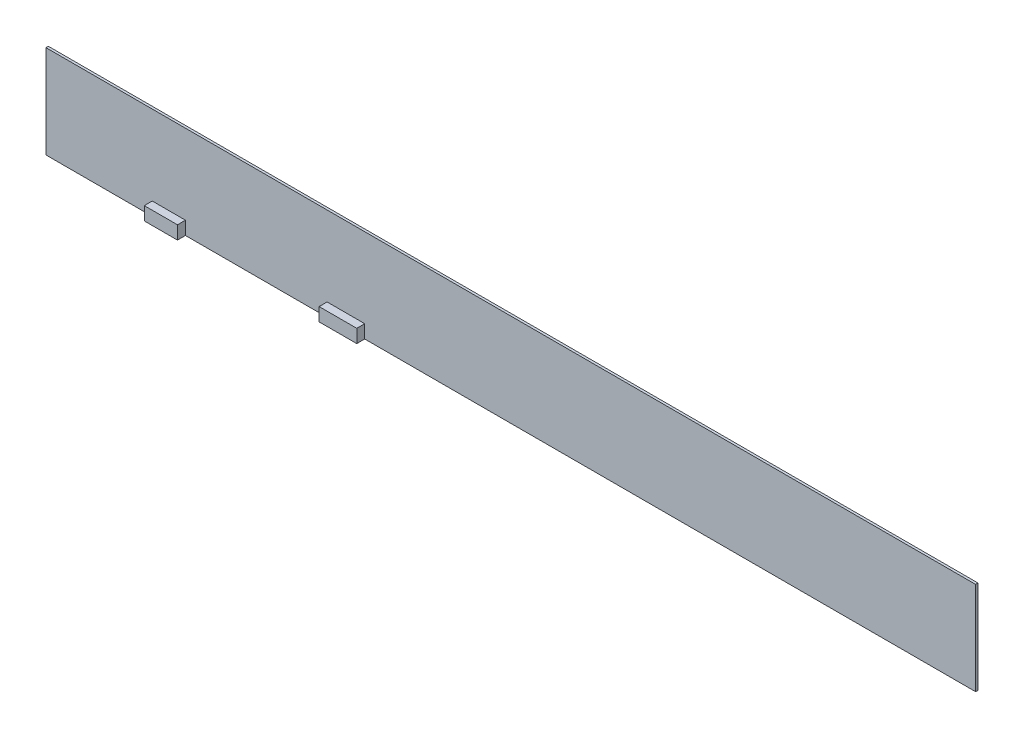
SolidWorks part; units mm, degrees
ref_plane "前视基准面" through (0, 0, 0) normal (0, 0, 1) x (1, 0, 0)
ref_plane "上视基准面" through (0, 0, 0) normal (0, 1, 0) x (1, 0, 0)
ref_plane "右视基准面" through (0, 0, 0) normal (1, 0, 0) x (0, 0, -1)
other "Configuration Table"
sketch "草图1" plane through (0, 0, 0) normal (0, 0, 1) x (1, 0, 0)
  line L1 (0, 0) -> (2100, 0)
  line L2 (0, 0) -> (0, 210)
  line L3 (0, 210) -> (2100, 210)
  line L4 (2100, 0) -> (2100, 210)
  dimension "D1" = 2100
  dimension "D2" = 210
extrude "凸台-拉伸1" add sketch "草图1" along normal blind 5.4
sketch "草图2" plane through (0, 0, 5.4) normal (0, 0, 1) x (1, 0, 0)
  line L0 (0, 0) -> (2100, 0) construction
  line L1 (240, 0) -> (315, 0)
  line L2 (240, 0) -> (240, 30)
  line L3 (240, 30) -> (315, 30)
  line L4 (315, 0) -> (315, 30)
  line L5 (0, 210) -> (0, 0) construction
  line L7 (635, 0) -> (720, 0)
  line L8 (635, 0) -> (635, 30)
  line L9 (635, 30) -> (720, 30)
  line L10 (720, 0) -> (720, 30)
  dimension "D1" = 30
  dimension "D2" = 240
  dimension "D3" = 315
  dimension "D4" = 30
  dimension "D5" = 635
  dimension "D6" = 720
extrude "凸台-拉伸2" add sketch "草图2" along normal blind 18
sketch "草图4" plane through (0, 0, 0) normal (0, 0, -1) x (-1, 0, 0)
  line L0 (0, 0) -> (-2100, 0) construction
  line L1 (-2034, 18) -> (-66, 18)
  line L2 (-2034, 18) -> (-2034, 200)
  line L3 (-2034, 200) -> (-66, 200)
  line L4 (-66, 18) -> (-66, 200)
  line L5 (-2100, 210) -> (0, 210) construction
  line L6 (0, 210) -> (0, 0) construction
  line L7 (-2100, 0) -> (-2100, 210) construction
  dimension "D1" = 18
  dimension "D2" = 10
  dimension "D3" = 66
  dimension "D4" = 66
extrude "凸台-拉伸3" add sketch "草图4" along normal blind 0.2
ref_plane "基准面1" through (0, 109, 0) normal (0, 1, 0) x (1, 0, 0)
